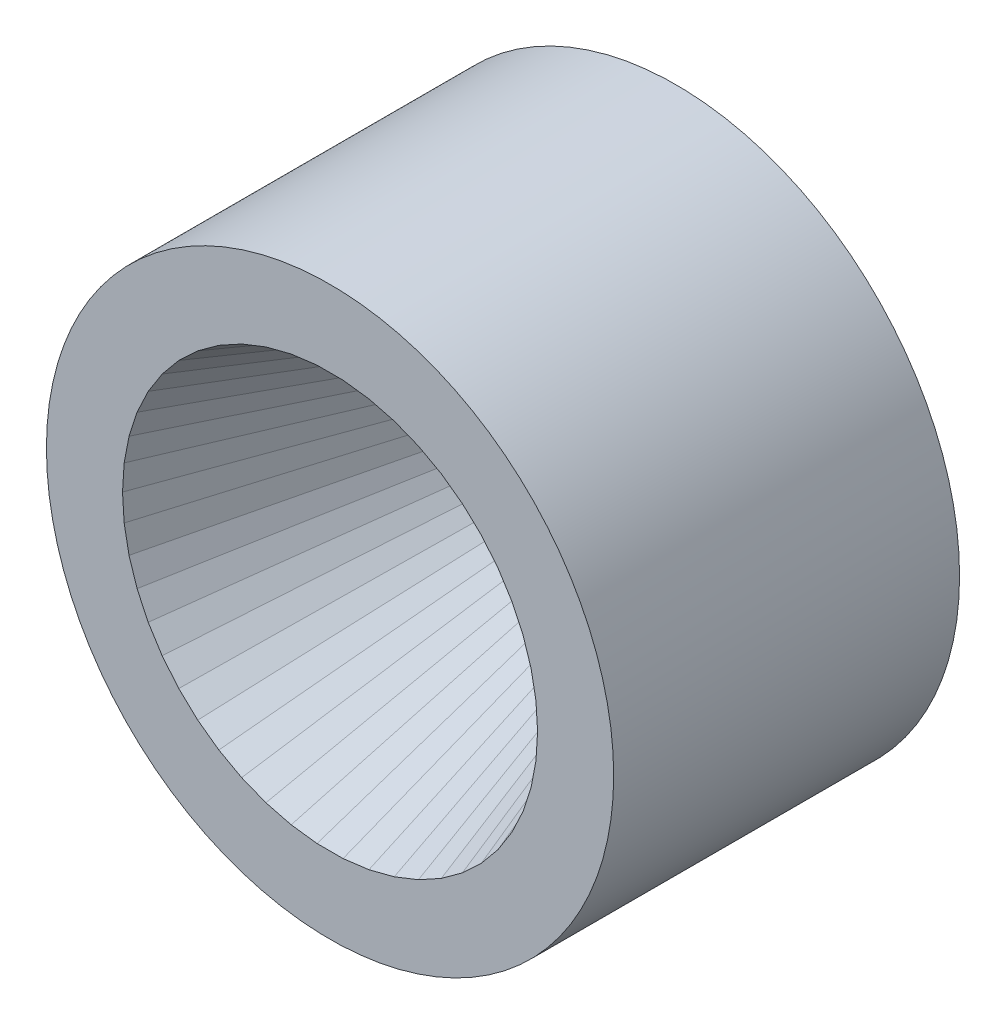
SolidWorks part; units mm, degrees
ref_plane "Plan de face" through (0, 0, 0) normal (0, 0, 1) x (1, 0, 0)
ref_plane "Plan de dessus" through (0, 0, 0) normal (0, 1, 0) x (1, 0, 0)
ref_plane "Plan de droite" through (0, 0, 0) normal (1, 0, 0) x (0, 0, -1)
ref_plane "Plan1" through (0, 0, 0) normal (0, 0, -1) x (-1, 0, 0)
sketch "Esquisse1" plane through (0, 0, 0) normal (0, 0, -1) x (-1, 0, 0)
  circle A0 centre (-4.1, 4.1) radius 4.1
extrude "Boss.-Extru.1" add sketch "Esquisse1" against normal blind 5
sketch "Esquisse2" plane through (0, 0, 5) normal (0, 0, 1) x (1, 0, 0)
  line L0 (7.0763, 4.476) -> (7.0057, 4.8461)
  line L1 (7.0057, 4.8461) -> (6.8893, 5.2044)
  line L2 (6.8893, 5.2044) -> (6.7289, 5.5453)
  line L3 (6.7289, 5.5453) -> (6.5271, 5.8634)
  line L4 (6.5271, 5.8634) -> (6.2869, 6.1536)
  line L5 (6.2869, 6.1536) -> (6.0123, 6.4115)
  line L6 (6.0123, 6.4115) -> (5.7075, 6.633)
  line L7 (5.7075, 6.633) -> (5.3773, 6.8145)
  line L8 (5.3773, 6.8145) -> (5.0271, 6.9532)
  line L9 (5.0271, 6.9532) -> (4.6621, 7.0469)
  line L10 (4.6621, 7.0469) -> (4.2884, 7.0941)
  line L11 (4.2884, 7.0941) -> (3.9116, 7.0941)
  line L12 (3.9116, 7.0941) -> (3.5379, 7.0469)
  line L13 (3.5379, 7.0469) -> (3.1729, 6.9532)
  line L14 (3.1729, 6.9532) -> (2.8227, 6.8145)
  line L15 (2.8227, 6.8145) -> (2.4925, 6.633)
  line L16 (2.4925, 6.633) -> (2.1877, 6.4115)
  line L17 (2.1877, 6.4115) -> (1.9131, 6.1536)
  line L18 (1.9131, 6.1536) -> (1.6729, 5.8634)
  line L19 (1.6729, 5.8634) -> (1.4711, 5.5453)
  line L20 (1.4711, 5.5453) -> (1.3107, 5.2044)
  line L21 (1.3107, 5.2044) -> (1.1943, 4.8461)
  line L22 (1.1943, 4.8461) -> (1.1237, 4.476)
  line L23 (1.1237, 4.476) -> (1.1, 4.1)
  line L24 (1.1, 4.1) -> (1.1237, 3.724)
  line L25 (1.1237, 3.724) -> (1.1943, 3.3539)
  line L26 (1.1943, 3.3539) -> (1.3107, 2.9956)
  line L27 (1.3107, 2.9956) -> (1.4711, 2.6547)
  line L28 (1.4711, 2.6547) -> (1.6729, 2.3366)
  line L29 (1.6729, 2.3366) -> (1.9131, 2.0464)
  line L30 (1.9131, 2.0464) -> (2.1877, 1.7885)
  line L31 (2.1877, 1.7885) -> (2.4925, 1.567)
  line L32 (2.4925, 1.567) -> (2.8227, 1.3855)
  line L33 (2.8227, 1.3855) -> (3.1729, 1.2468)
  line L34 (3.1729, 1.2468) -> (3.5379, 1.1531)
  line L35 (3.5379, 1.1531) -> (3.9116, 1.1059)
  line L36 (3.9116, 1.1059) -> (4.2884, 1.1059)
  line L37 (4.2884, 1.1059) -> (4.6621, 1.1531)
  line L38 (4.6621, 1.1531) -> (5.0271, 1.2468)
  line L39 (5.0271, 1.2468) -> (5.3773, 1.3855)
  line L40 (5.3773, 1.3855) -> (5.7075, 1.567)
  line L41 (5.7075, 1.567) -> (6.0123, 1.7885)
  line L42 (6.0123, 1.7885) -> (6.2869, 2.0464)
  line L43 (6.2869, 2.0464) -> (6.5271, 2.3366)
  line L44 (6.5271, 2.3366) -> (6.7289, 2.6547)
  line L45 (6.7289, 2.6547) -> (6.8893, 2.9956)
  line L46 (6.8893, 2.9956) -> (7.0057, 3.3539)
  line L47 (7.0057, 3.3539) -> (7.0763, 3.724)
  line L48 (7.0763, 3.724) -> (7.1, 4.1)
  line L49 (7.1, 4.1) -> (7.0763, 4.476)
extrude "Enlèv. mat.-Extru.1" cut sketch "Esquisse2" against normal through all
draft "Dépouille1" type of draft neutral plane draft angle 19.964 faces to draft 50 face at (7.041, 4.661, 2.5) face at (6.9475, 5.0252, 2.5) face at (6.8091, 5.3748, 2.5) face at (6.628, 5.7043, 2.5) face at (6.407, 6.0085, 2.5) face at (6.1496, 6.2826, 2.5) face at (5.8599, 6.5223, 2.5) face at (5.5424, 6.7237, 2.5) face at (5.2022, 6.8838, 2.5) face at (4.8446, 7, 2.5) face at (4.4753, 7.0705, 2.5) face at (4.1, 7.0941, 2.5) face at (3.7247, 7.0705, 2.5) face at (3.3554, 7, 2.5) face at (2.9978, 6.8838, 2.5) face at (2.6576, 6.7237, 2.5) face at (2.3401, 6.5223, 2.5) face at (2.0504, 6.2826, 2.5) face at (1.793, 6.0085, 2.5) face at (1.572, 5.7043, 2.5) face at (1.3909, 5.3748, 2.5) face at (1.2525, 5.0252, 2.5) face at (1.159, 4.661, 2.5) face at (1.1118, 4.288, 2.5) face at (1.1118, 3.912, 2.5) face at (1.159, 3.539, 2.5) face at (1.2525, 3.1748, 2.5) face at (1.3909, 2.8252, 2.5) face at (1.572, 2.4957, 2.5) face at (1.793, 2.1915, 2.5) face at (2.0504, 1.9174, 2.5) face at (2.3401, 1.6777, 2.5) face at (2.6576, 1.4763, 2.5) face at (2.9978, 1.3162, 2.5) face at (3.3554, 1.2, 2.5) face at (3.7247, 1.1295, 2.5) face at (4.1, 1.1059, 2.5) face at (4.4753, 1.1295, 2.5) face at (4.8446, 1.2, 2.5) face at (5.2022, 1.3162, 2.5) face at (5.5424, 1.4763, 2.5) face at (5.8599, 1.6777, 2.5) face at (6.1496, 1.9174, 2.5) face at (6.407, 2.1915, 2.5) face at (6.628, 2.4957, 2.5) face at (6.8091, 2.8252, 2.5) face at (6.9475, 3.1748, 2.5) face at (7.041, 3.539, 2.5) face at (7.0882, 3.912, 2.5) face at (7.0882, 4.288, 2.5) neutral plane through (4.1, 4.1, 5) neutral plane normal (0, 0, 1) parameters "D1"=19.964
